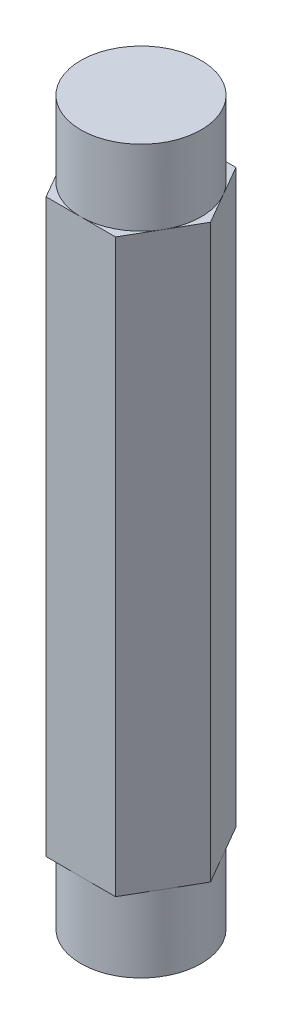
SolidWorks part; units mm, degrees
ref_plane "Front Plane" through (0, 0, 0) normal (0, 0, 1) x (1, 0, 0)
ref_plane "Top Plane" through (0, 0, 0) normal (0, 1, 0) x (1, 0, 0)
ref_plane "Right Plane" through (0, 0, 0) normal (1, 0, 0) x (0, 0, -1)
sketch "Sketch1" plane through (0, 0, 0) normal (0, 1, 0) x (1, 0, 0)
  line L1 (3.6662, -6.35) -> (7.3323, 0)
  line L2 (7.3323, 0) -> (3.6662, 6.35)
  line L3 (3.6662, 6.35) -> (-3.6662, 6.35)
  line L4 (-3.6662, 6.35) -> (-7.3323, 0)
  line L5 (-7.3323, 0) -> (-3.6662, -6.35)
  line L6 (-3.6662, -6.35) -> (3.6662, -6.35)
  circle A0 centre (0, 0) radius 6.35 construction
  dimension "D1" = 12.7
extrude "Boss-Extrude1" add sketch "Sketch1" along normal mid plane 76.2
sketch "Sketch2" plane through (0, 38.1, 0) normal (0, 1, 0) x (1, 0, 0)
  circle A0 centre (0, 0) radius 6.35
  dimension "D1" = 12.7
extrude "Cut-Extrude1" cut sketch "Sketch2" against normal blind 7.9502 flip side to cut
mirror "Mirror1" about plane through (0, 0, 0) normal (0, 1, 0) of "Cut-Extrude1"
